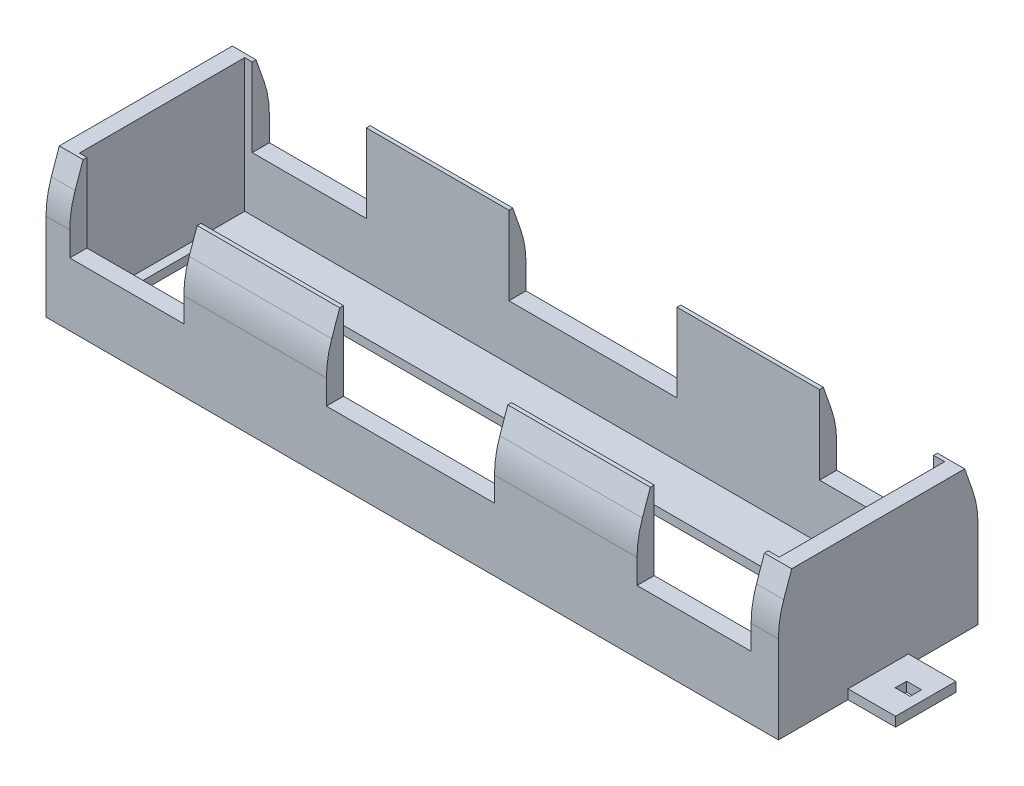
SolidWorks part; units mm, degrees
ref_plane "Plan de face" through (0, 0, 0) normal (0, 0, 1) x (1, 0, 0)
ref_plane "Plan de dessus" through (0, 0, 0) normal (0, 1, 0) x (1, 0, 0)
ref_plane "Plan de droite" through (0, 0, 0) normal (1, 0, 0) x (0, 0, -1)
sketch "Esquisse1" plane through (0, 0, 0) normal (1, 0, 0) x (0, 0, -1)
  line L0 (0, 0) -> (10.5, 0) construction
  line L1 (0, 0) -> (-10.5, 0) construction
  line L2 (10.5, 0) -> (10.5, 14.9) construction
  line L3 (-10.5, 0) -> (-10.5, 14.9) construction
  line L4 (-10.5, 14.9) -> (10.5, 14.9) construction
  line L5 (-10.5, 14.9) -> (-9.1, 14.9) construction
  line L6 (10.5, 14.9) -> (9.1, 14.9) construction
  line L7 (-10.5, 14.9) -> (-10.5, 10.9) construction
  line L8 (10.5, 14.9) -> (10.5, 10.9) construction
  line L9 (-10.5, 10.9) -> (-9.1, 14.9)
  line L10 (-9.1, 14.9) -> (9.1, 14.9)
  line L11 (9.1, 14.9) -> (10.5, 10.9)
  line L12 (10.5, 10.9) -> (10.5, 0)
  line L13 (10.5, 0) -> (-10.5, 0)
  line L14 (-10.5, 0) -> (-10.5, 10.9)
extrude "Boss.-Extru.1" add sketch "Esquisse1" along normal blind 77.05
sketch "Esquisse3" plane through (0, 0, 0) normal (0, -1, 0) x (1, 0, 0)
  line L0 (77.05, 10.5) -> (77.05, -10.5) construction
  line L1 (5, -3.175) -> (-5, -3.175)
  line L2 (5, -3.175) -> (5, 3.175)
  line L3 (5, 3.175) -> (-5, 3.175)
  line L4 (-5, -3.175) -> (-5, 3.175)
  line L5 (5, -3.175) -> (-5, 3.175) construction
  line L6 (5, 3.175) -> (-5, -3.175) construction
  line L7 (72.05, -3.175) -> (82.05, -3.175)
  line L8 (72.05, -3.175) -> (72.05, 3.175)
  line L9 (72.05, 3.175) -> (82.05, 3.175)
  line L10 (82.05, -3.175) -> (82.05, 3.175)
  line L11 (72.05, -3.175) -> (82.05, 3.175) construction
  line L12 (72.05, 3.175) -> (82.05, -3.175) construction
  point P0 (0, 0)
  point P6 (77.05, 0)
  dimension "D1" = 6.35
  dimension "D2" = 10
  dimension "D3" = 10
extrude "Boss.-Extru.2" add sketch "Esquisse3" against normal blind 1
sketch "Esquisse5" plane through (0, 0, 0) normal (0, -1, 0) x (1, 0, 0)
  line L1 (-4.1671, -0.5988) -> (-2.6278, -0.5988)
  line L2 (-4.1671, -0.5988) -> (-4.1671, 0.5988)
  line L3 (-4.1671, 0.5988) -> (-2.6278, 0.5988)
  line L4 (-2.6278, -0.5988) -> (-2.6278, 0.5988)
  line L5 (-4.1671, -0.5988) -> (-2.6278, 0.5988) construction
  line L6 (-4.1671, 0.5988) -> (-2.6278, -0.5988) construction
  line L7 (79.4389, -0.5988) -> (81.0042, -0.5988)
  line L8 (79.4389, -0.5988) -> (79.4389, 0.5988)
  line L9 (79.4389, 0.5988) -> (81.0042, 0.5988)
  line L10 (81.0042, -0.5988) -> (81.0042, 0.5988)
  line L11 (79.4389, -0.5988) -> (81.0042, 0.5988) construction
  line L12 (79.4389, 0.5988) -> (81.0042, -0.5988) construction
  point P0 (-3.3975, 0)
  point P5 (80.2215, 0)
extrude "Enlèv. mat.-Extru.1" cut sketch "Esquisse5" against normal blind 1
sketch "Esquisse6" plane through (0, 14.9, 0) normal (0, 1, 0) x (1, 0, 0)
  line L0 (0, 9.1) -> (77.05, -9.1) construction
  line L1 (77.05, -9.1) -> (0, -9.1) construction
  line L2 (77.05, 9.1) -> (0, -9.1) construction
  line L4 (1.709, -8.6963) -> (75.341, -8.6963)
  line L5 (1.709, -8.6963) -> (1.709, 8.6963)
  line L6 (1.709, 8.6963) -> (75.341, 8.6963)
  line L7 (75.341, -8.6963) -> (75.341, 8.6963)
  line L8 (1.709, -8.6963) -> (75.341, 8.6963) construction
  line L9 (1.709, 8.6963) -> (75.341, -8.6963) construction
  point P9 (38.525, 0)
extrude "Enlèv. mat.-Extru.2" cut sketch "Esquisse6" against normal blind 14
sketch "Esquisse7" plane through (0, 14.9, 0) normal (0, 1, 0) x (1, 0, 0)
  line L0 (1.709, 8.6963) -> (75.341, -8.6963) construction
  line L1 (1.709, -8.6963) -> (75.341, -8.6963) construction
  line L2 (1.709, -8.6963) -> (75.341, -8.6963) construction
  line L3 (75.341, 8.6963) -> (1.709, -8.6963) construction
  line L4 (1.709, 8.6963) -> (1.709, -8.6963) construction
  line L6 (2.6622, -3.498) -> (74.3878, -3.498)
  line L7 (2.6622, -3.498) -> (2.6622, 3.498)
  line L8 (2.6622, 3.498) -> (74.3878, 3.498)
  line L9 (74.3878, -3.498) -> (74.3878, 3.498)
  line L10 (2.6622, -3.498) -> (74.3878, 3.498) construction
  line L11 (2.6622, 3.498) -> (74.3878, -3.498) construction
  point P12 (38.525, 0)
extrude "Enlèv. mat.-Extru.3" cut sketch "Esquisse7" against normal blind 16
sketch "Esquisse8" plane through (0, 0, 10.5) normal (0, 0, 1) x (1, 0, 0)
  line L0 (0, 10.9) -> (2.5, 10.9) construction
  line L1 (77.05, 10.9) -> (0, 10.9) construction
  line L2 (77.05, 10.9) -> (74.1811, 10.9) construction
  line L3 (0, 10.9) -> (0, 0) construction
  line L4 (0, 6.6403) -> (77.05, 6.6403) construction
  line L5 (77.05, 10.9) -> (77.05, 0) construction
  line L6 (2.5, 10.9) -> (14.5, 10.9) construction
  line L7 (74.1811, 10.9) -> (62.1811, 10.9) construction
  line L8 (14.5, 10.9) -> (29.5, 10.9) construction
  line L9 (62.1811, 10.9) -> (47.1811, 10.9) construction
  line L10 (2.5, 6.6403) -> (2.5, 14.9)
  line L11 (77.05, 14.9) -> (0, 14.9) construction
  line L12 (2.5, 14.9) -> (14.5, 14.9)
  line L13 (14.5, 14.9) -> (14.5, 6.6403)
  line L14 (14.5, 6.6403) -> (2.5, 6.6403)
  line L15 (29.5, 6.6403) -> (29.5, 14.9)
  line L16 (29.5, 14.9) -> (47.1811, 14.9)
  line L17 (47.1811, 14.9) -> (47.1811, 6.6403)
  line L18 (47.1811, 6.6403) -> (29.5, 6.6403)
  line L19 (62.1811, 6.6403) -> (62.1811, 14.9)
  line L20 (62.1811, 14.9) -> (74.1811, 14.9)
  line L21 (74.1811, 14.9) -> (74.1811, 6.6403)
  line L22 (74.1811, 6.6403) -> (62.1811, 6.6403)
  dimension "D1" = 12
  dimension "D2" = 12
  dimension "D3" = 15
  dimension "D4" = 15
extrude "Enlèv. mat.-Extru.4" cut sketch "Esquisse8" against normal blind 23
fillet "Congé1" radius 10 8 edges at (1.25, 10.9, -10.5) (22, 10.9, -10.5) (54.6811, 10.9, -10.5) (75.6156, 10.9, -10.5) (75.6156, 10.9, 10.5) (54.6811, 10.9, 10.5) (22, 10.9, 10.5) (1.25, 10.9, 10.5)
